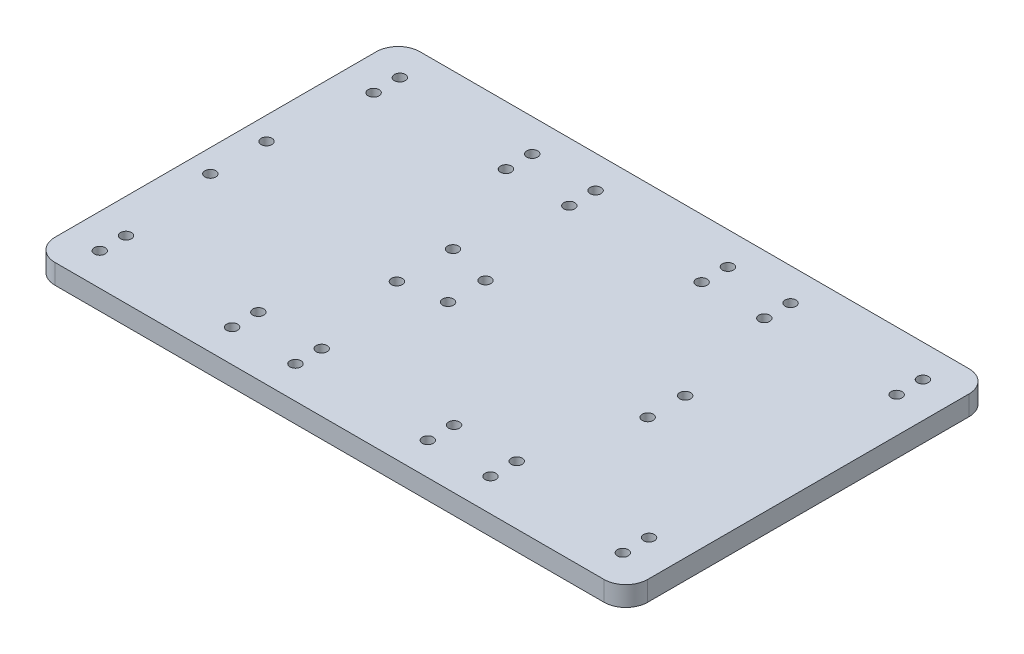
SolidWorks part; units mm, degrees
ref_plane "Front Plane" through (0, 0, 0) normal (0, 0, 1) x (1, 0, 0)
ref_plane "Top Plane" through (0, 0, 0) normal (0, 1, 0) x (1, 0, 0)
ref_plane "Right Plane" through (0, 0, 0) normal (1, 0, 0) x (0, 0, -1)
sketch "Sketch1" plane through (0, 0, 0) normal (0, 1, 0) x (1, 0, 0)
  line L1 (0, 0) -> (190, 0)
  line L2 (0, 0) -> (0, 117)
  line L3 (0, 117) -> (190, 117)
  line L4 (190, 0) -> (190, 117)
  dimension "D1" = 190
  dimension "D2" = 117
extrude "Boss-Extrude1" add sketch "Sketch1" along normal blind 6.35
sketch "SS Holes" plane through (0, 0, 0) normal (0, -1, 0) x (1, 0, 0)
  circle A0 centre (178.6182, -98.18) radius 1.75
  circle A1 centre (178.6182, -106.6) radius 1.75
  circle A2 centre (136.1982, -98.18) radius 1.75
  circle A3 centre (136.1982, -106.6) radius 1.75
  circle A4 centre (116.1047, -106.6) radius 1.75
  circle A5 centre (116.1047, -98.18) radius 1.75
  circle A6 centre (178.6182, -18.82) radius 1.75
  circle A7 centre (178.6182, -10.4) radius 1.75
  circle A8 centre (136.1982, -18.82) radius 1.75
  circle A9 centre (136.1982, -10.4) radius 1.75
  circle A10 centre (116.1047, -18.82) radius 1.75
  circle A11 centre (116.1047, -10.4) radius 1.75
  circle A12 centre (145, -52) radius 1.75
  circle A13 centre (145, -64) radius 1.75
  circle A14 centre (73.6847, -10.4) radius 1.75
  circle A15 centre (73.6847, -18.82) radius 1.75
  circle A16 centre (53.3716, -18.82) radius 1.75
  circle A17 centre (53.3716, -10.4) radius 1.75
  circle A18 centre (81, -52) radius 1.75
  circle A19 centre (81, -64) radius 1.75
  circle A20 centre (73.6847, -98.18) radius 1.75
  circle A21 centre (73.6847, -106.6) radius 1.75
  circle A22 centre (53.3716, -106.6) radius 1.75
  circle A23 centre (53.3716, -98.18) radius 1.75
  circle A24 centre (10.9516, -106.6) radius 1.75
  circle A25 centre (10.9516, -98.18) radius 1.75
  circle A26 centre (67.0912, -67.5) radius 1.75
  circle A27 centre (67.0912, -49.5) radius 1.75
  circle A28 centre (7.3128, -49.5) radius 1.75
  circle A29 centre (7.3128, -67.5) radius 1.75
  circle A30 centre (10.9516, -18.82) radius 1.75
  circle A31 centre (10.9516, -10.4) radius 1.75
  dimension "D1" = 3.5
  dimension "D2" = 3.5
  dimension "D3" = 3.5
sketch "Logo" plane through (0, 0, 0) normal (0, 1, 0) x (1, 0, 0)
  line L1 (29.955, 39.4815) -> (29.955, 75.4815)
  line L2 (33.955, 35.4815) -> (38.7909, 35.4815)
  line L3 (42.7909, 39.4815) -> (42.7909, 75.4815)
  line L4 (33.955, 79.4815) -> (38.7909, 79.4815)
  line L12 (164.4238, 79.0838) -> (164.4238, 34.7006) construction
  line L13 (171.6226, 45.9805) -> (171.6226, 65.9805)
  line L14 (175.6226, 41.9805) -> (178.2178, 41.9805)
  line L15 (182.2178, 45.9805) -> (182.2178, 65.9805)
  line L16 (175.6226, 69.9805) -> (178.2178, 69.9805)
  arc A0 (38.7909, 35.4815) -> (42.7909, 39.4815) centre (38.7909, 39.4815) ccw
  arc A1 (29.955, 75.4815) -> (33.955, 79.4815) centre (33.955, 75.4815) cw
  arc A4 (29.955, 39.4815) -> (33.955, 35.4815) centre (33.955, 39.4815) ccw
  arc A5 (42.7909, 75.4815) -> (38.7909, 79.4815) centre (38.7909, 75.4815) ccw
  arc A8 (36.75, 59.4109) -> (48.8318, 59.4109) centre (42.7909, 59.4109) ccw
  arc A9 (36.0874, 46.7576) -> (23.8249, 46.5895) centre (29.955, 46.7576) cw
  arc A10 (35.466, 71.7245) -> (24.4443, 71.7371) centre (29.955, 71.5869) cw
  arc A18 (178.2178, 41.9805) -> (182.2178, 45.9805) centre (178.2178, 45.9805) ccw
  arc A19 (171.6226, 65.9805) -> (175.6226, 69.9805) centre (175.6226, 65.9805) cw
  arc A20 (171.6226, 45.9805) -> (175.6226, 41.9805) centre (175.6226, 45.9805) ccw
  arc A21 (182.2178, 65.9805) -> (178.2178, 69.9805) centre (178.2178, 65.9805) ccw
  arc A22 (178.8617, 57.0523) -> (185.5739, 57.0523) centre (182.2178, 57.0523) ccw
  arc A23 (174.9496, 51.3124) -> (168.2969, 51.2207) centre (171.6226, 51.3124) cw
  arc A24 (174.9489, 62.5356) -> (168.2962, 62.5356) centre (171.6226, 62.4488) cw
  text T0 "<b>RHex Mini</b>" font "Constantia" height 6
  dimension "D3" = 4
extrude "Cut-Extrude1" cut sketch "SS Holes" against normal through all
fillet "Fillet1" radius 7 4 edges at (0, 3.175, -117) (0, 3.175, 0) (190, 3.175, 0) (190, 3.175, -117)
